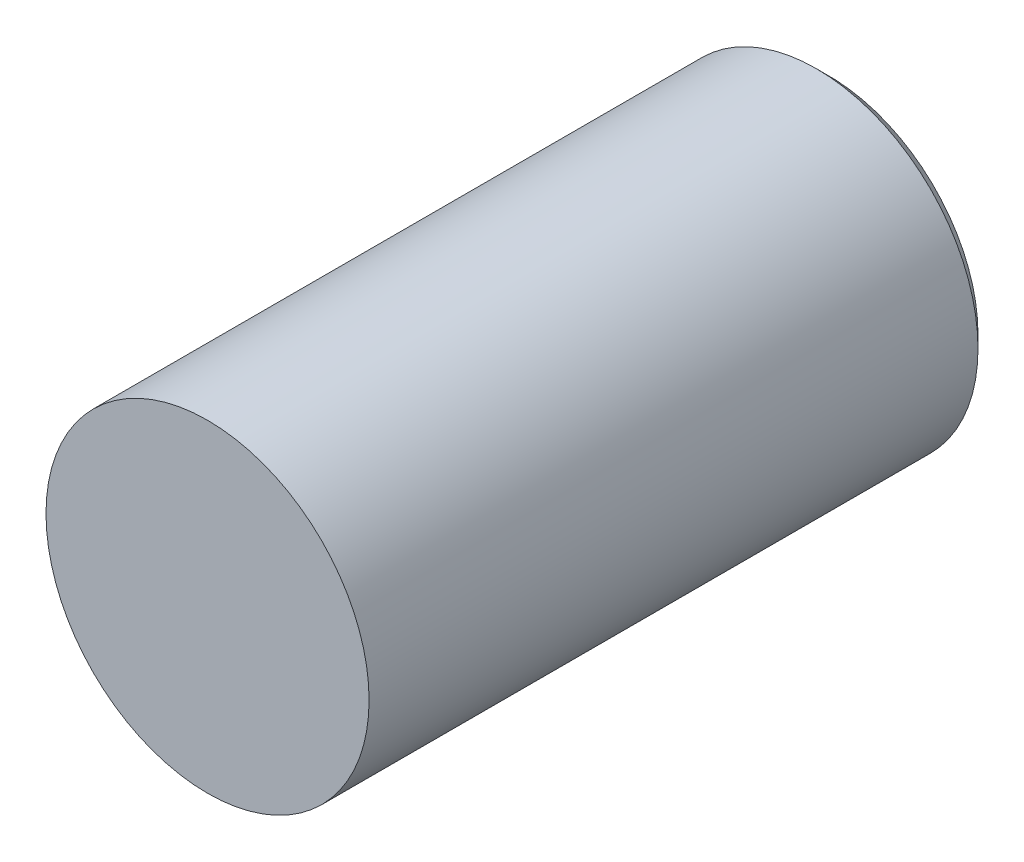
SolidWorks part; units mm, degrees
ref_plane "前视基准面" through (0, 0, 0) normal (0, 0, 1) x (1, 0, 0)
ref_plane "上视基准面" through (0, 0, 0) normal (0, 1, 0) x (1, 0, 0)
ref_plane "右视基准面" through (0, 0, 0) normal (1, 0, 0) x (0, 0, -1)
sketch "草图1" plane through (0, 0, 0) normal (0, 0, 1) x (1, 0, 0)
  circle A0 centre (0, 0) radius 2.6
  circle A1 centre (0, 0) radius 3.9
  dimension "D1" = 5.2
  dimension "D2" = 7.8
extrude "凸台-拉伸1" add sketch "草图1" along normal blind 15
sketch "草图2" plane through (0, 0, 15) normal (0, 0, 1) x (1, 0, 0)
  circle A0 centre (0, 0) radius 2.6
extrude "凸台-拉伸2" add sketch "草图2" against normal blind 7
sketch "草图3" plane through (0, 0, 8) normal (0, 0, -1) x (-1, 0, 0)
  line L0 (0, 2.6) -> (0, -2.6) construction
  line L1 (-1.6, 2.0494) -> (-1.6, -2.0494)
  line L2 (1.6, 2.0494) -> (1.6, -2.0494)
  circle A0 centre (0, 0) radius 2.6 construction
  circle A1 centre (0, 0) radius 2.6 construction
  arc A2 (-1.6, 2.0494) -> (-1.6, -2.0494) centre (0, 0) ccw
  arc A3 (1.6, 2.0494) -> (1.6, -2.0494) centre (0, 0) cw
  circle M4 centre (0, 0) radius 2.6
  dimension "D1" = 3.2
extrude "凸台-拉伸3" add sketch "草图3" along normal blind 6.2 contours L1 M4 | L2 M4
chamfer "倒角1" distance 0.3 angle 45 1 edges at (2.6, 0, 0)
chamfer "倒角2" distance 0.3 angle 45 1 edges at (3.9, 0, 0)
chamfer "倒角3" distance 0.3 angle 45 2 edges at (-1.6, 0, 1.8) (1.6, 0, 1.8)
